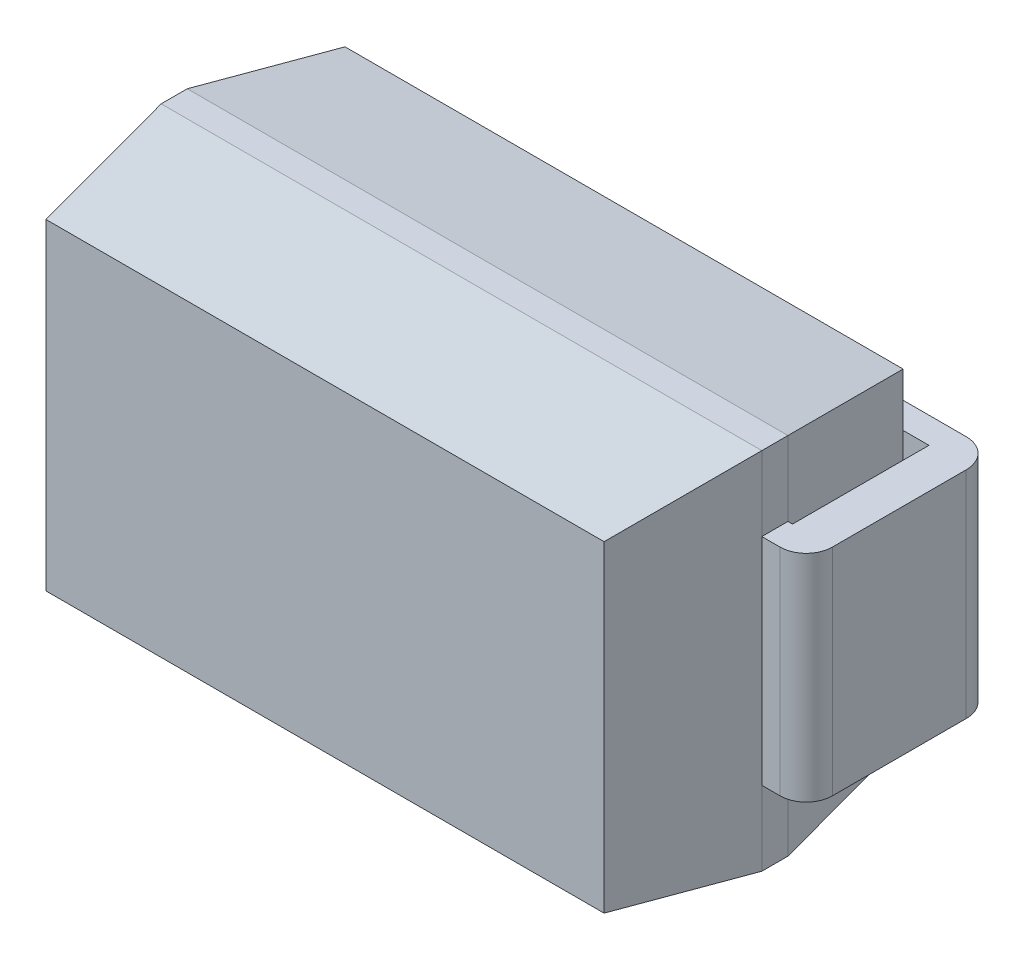
SolidWorks part; units mm, degrees
other "Детальный элемент1"
ref_plane "Спереди" through (0, 0, 0) normal (0, 0, 1) x (1, 0, 0)
ref_plane "Сверху" through (0, 0, 0) normal (0, 1, 0) x (1, 0, 0)
ref_plane "Справа" through (0, 0, 0) normal (1, 0, 0) x (0, 0, -1)
ref_plane "Плоскость1" through (0, 0, 0.2) normal (0, 0, 1) x (1, 0, 0)
sketch "Эскиз1" plane through (0, 0, 0.2) normal (0, 0, 1) x (1, 0, 0)
  line L1 (-2.3, 1.395) -> (2.3, 1.395)
  line L2 (-2.3, 1.395) -> (-2.3, -1.395)
  line L3 (-2.3, -1.395) -> (2.3, -1.395)
  line L4 (2.3, 1.395) -> (2.3, -1.395)
  line L5 (-2.3, 1.395) -> (2.3, -1.395) construction
  line L6 (-2.3, -1.395) -> (2.3, 1.395) construction
  point P0 (0, 0)
  dimension "D1" = 4.6
  dimension "D2" = 2.79
extrude "Бобышка-Вытянуть1" add sketch "Эскиз1" along normal blind 2.29
chamfer "Фаска1" distance 1.045 distance2 0.163 4 edges at (0, 1.395, 2.49) (2.3, 0, 2.49) (0, -1.395, 2.49) (-2.3, 0, 2.49)
chamfer "Фаска2" distance 0.163 distance2 1.045 4 edges at (2.3, 0, 0.2) (0, 1.395, 0.2) (0, -1.395, 0.2) (-2.3, 0, 0.2)
sketch "Эскиз2" plane through (0, 0, 0) normal (0, 1, 0) x (1, 0, 0)
  line L0 (-2.335, -0.2) -> (-2.335, -1.245)
  line L1 (-1.12, 0) -> (-2.42, 0)
  line L2 (-1.12, 0) -> (-1.12, -0.2)
  line L3 (-1.12, -0.2) -> (-2.335, -0.2)
  line L5 (-2.64, -1.245) -> (-2.64, -0.22)
  line L6 (-2.335, -1.245) -> (-2.3, -1.245)
  line L7 (-2.3, -1.245) -> (-2.3, -1.445)
  line L8 (-2.3, -1.445) -> (-2.44, -1.445)
  line L9 (-2.3, -1.445) -> (-2.3, -1.245) construction
  arc A2 (-2.44, -1.445) -> (-2.64, -1.245) centre (-2.44, -1.245) cw
  arc A3 (-2.42, 0) -> (-2.64, -0.22) centre (-2.42, -0.22) ccw
  point P4 (0, 0)
  dimension "D3" = 0.22
  dimension "D5" = 0.2
  dimension "D1" = 0.2
  dimension "D2" = 0.305
  dimension "D4" = 1.52
  dimension "D6" = 0.34
extrude "Бобышка-Вытянуть2" add sketch "Эскиз2" along normal blind 0.825 and the other way blind 0.825 separate body
mirror "Зеркальное отражение1" about plane through (0, 0, 0) normal (1, 0, 0) of bodies 108
